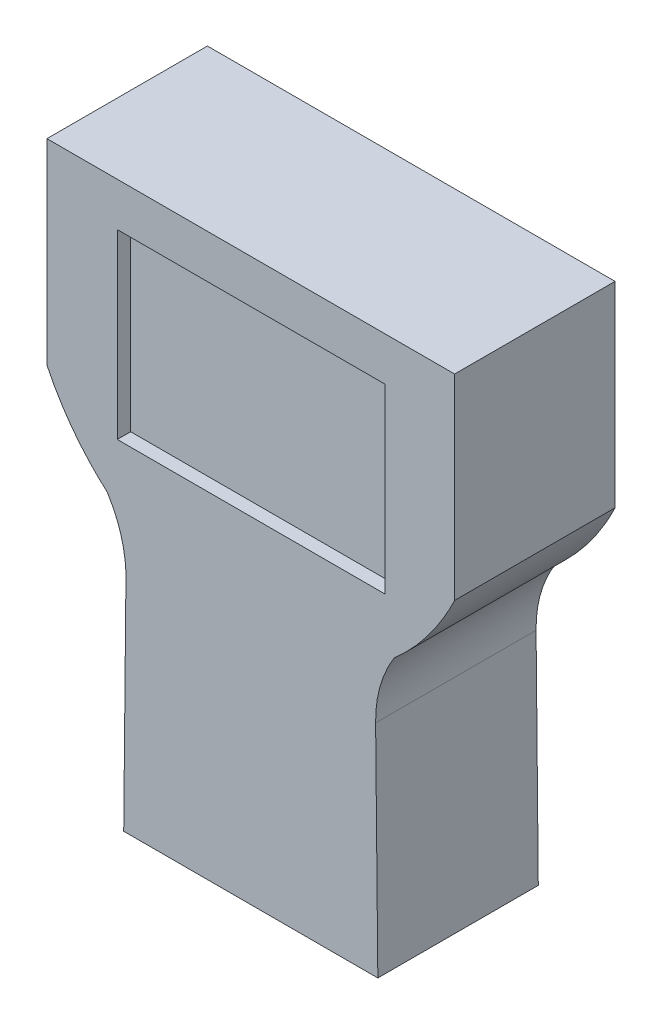
SolidWorks part; units mm, degrees
ref_plane "Front Plane" through (0, 0, 0) normal (0, 0, 1) x (1, 0, 0)
ref_plane "Top Plane" through (0, 0, 0) normal (0, 1, 0) x (1, 0, 0)
ref_plane "Right Plane" through (0, 0, 0) normal (1, 0, 0) x (0, 0, -1)
sketch "Sketch1" plane through (0, 0, 0) normal (0, 0, 1) x (1, 0, 0)
  line L0 (31.3095, -34.4903) -> (31.7239, -75.5903)
  line L1 (46.0788, 29.3855) -> (46.0788, -7.2771)
  line L2 (31.7239, -75.5903) -> (-15.7896, -75.5903)
  line L3 (-30.1445, 29.3855) -> (-30.1445, -7.2771)
  line L4 (-30.1445, 29.3855) -> (25.0463, 29.3855)
  line L5 (-15.3753, -34.4903) -> (-15.7896, -75.5903)
  line L6 (25.0463, 29.3855) -> (46.0788, 29.3855)
  spline S0 degree 2 poles (46.0788, -7.2771) (41.9284, -15.9453) (34.8118, -22.1982) knots 0 0 0 1 1 1
  spline S1 degree 3 poles (-18.8775, -22.1982) (-16.4983, -25.9922) (-15.3309, -30.0896) (-15.3753, -34.4903) knots 0 0 0 0 1 1 1 1
  spline S2 degree 3 poles (34.8118, -22.1982) (32.4325, -25.9922) (31.2651, -30.0896) (31.3095, -34.4903) knots 0 0 0 0 1 1 1 1
  spline S3 degree 2 poles (-30.1445, -7.2771) (-25.9942, -15.9453) (-18.8775, -22.1982) knots 0 0 0 1 1 1
extrude "Boss-Extrude1" add sketch "Sketch1" along normal blind 30
sketch "Sketch2" plane through (0, 0, 30) normal (0, 0, 1) x (1, 0, 0)
  line L1 (-16.992, 21.2398) -> (33.1032, 21.2398)
  line L2 (-16.992, 21.2398) -> (-16.992, -12.747)
  line L3 (-16.992, -12.747) -> (33.1032, -12.747)
  line L4 (33.1032, 21.2398) -> (33.1032, -12.747)
extrude "Cut-Extrude1" cut sketch "Sketch2" against normal blind 2.5 contours L2 L1 L4 L3
